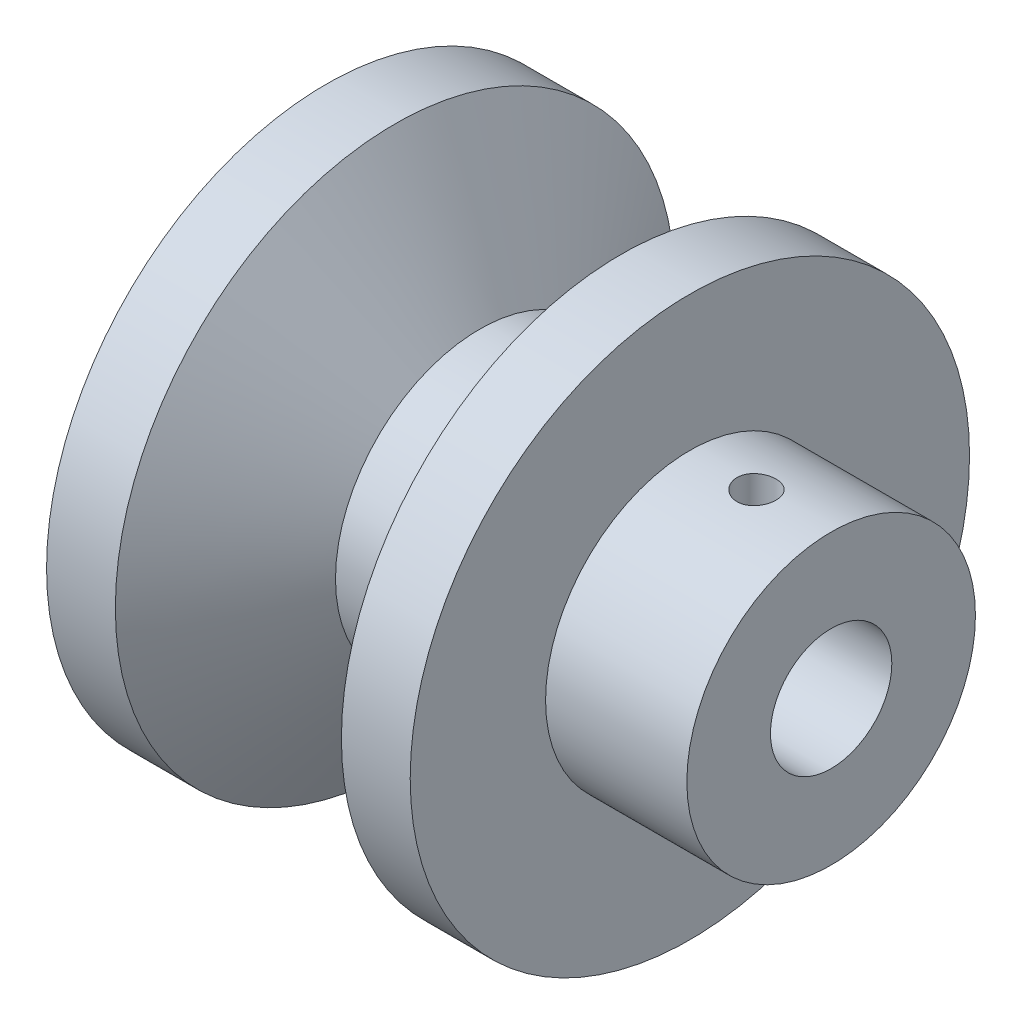
SolidWorks part; units mm, degrees
ref_plane "前基準面" through (0, 0, 0) normal (0, 0, 1) x (1, 0, 0)
ref_plane "上基準面" through (0, 0, 0) normal (0, 1, 0) x (1, 0, 0)
ref_plane "右基準面" through (0, 0, 0) normal (1, 0, 0) x (0, 0, -1)
sketch "草圖1" plane through (0, 0, 0) normal (0, 0, 1) x (1, 0, 0)
  line L0 (0, 0) -> (0, 19.795)
  line L1 (0, 19.795) -> (4.87, 19.795)
  line L2 (4.87, 19.795) -> (10.87, 10.2139)
  line L3 (10.87, 10.2139) -> (14.87, 10.2139)
  line L4 (14.87, 10.2139) -> (20.87, 19.795)
  line L5 (20.87, 19.795) -> (25.74, 19.795)
  line L6 (25.74, 19.795) -> (25.74, 10.2139)
  line L7 (25.74, 10.2139) -> (35.74, 10.2139)
  line L8 (35.74, 10.2139) -> (35.74, 0)
  line L9 (-743.1564, 0) -> (36475.4845, 0) construction
  line L10 (0, 0) -> (35.74, 0)
  dimension "D1" = 19.795
  dimension "D2" = 4.87
  dimension "D3" = 6
  dimension "D4" = 4
  dimension "D5" = 6
  dimension "D6" = 4.87
  dimension "D7" = 10
revolve "旋轉1" add sketch "草圖1" angle 360 about L9
ref_plane "平面1" through (0, 12, 0) normal (0, 1, 0) x (1, 0, 0)
sketch "草圖2" plane through (0, 12, 0) normal (0, 1, 0) x (1, 0, 0)
  circle A0 centre (30.4565, 0) radius 1.385
  dimension "D1" = 2.77
extrude "除料-伸長1" cut sketch "草圖2" against normal blind 10
sketch "草圖3" plane through (35.74, 0, 0) normal (1, 0, 0) x (0, 0, -1)
  circle A0 centre (0, 0) radius 4.295
  dimension "D1" = 8.59
extrude "除料-伸長2" cut sketch "草圖3" against normal blind 10
sketch "草圖4" plane through (25.74, 0, 0) normal (1, 0, 0) x (0, 0, -1)
  line L1 (-2.7569, 4.7211) -> (2.5877, 4.7211)
  line L2 (-2.7569, 4.7211) -> (-2.7569, 3.428)
  line L3 (-2.7569, 3.428) -> (2.5877, 3.428)
  line L4 (2.5877, 4.7211) -> (2.5877, 3.428)
  circle A0 centre (0, 0) radius 4.295 construction
extrude "填料-伸長1" add sketch "草圖4" along normal blind 7
sketch "草圖6" plane through (0, 4.7211, 0) normal (0, 1, 0) x (1, 0, 0)
  line L0 (-970.9285, 0) -> (49029.0715, 0) construction
  line L1 (30.4565, -998.615) -> (30.4565, 49001.385) construction
  circle A0 centre (30.4565, 0) radius 1.385
extrude "除料-伸長3" cut sketch "草圖6" against normal blind 7
